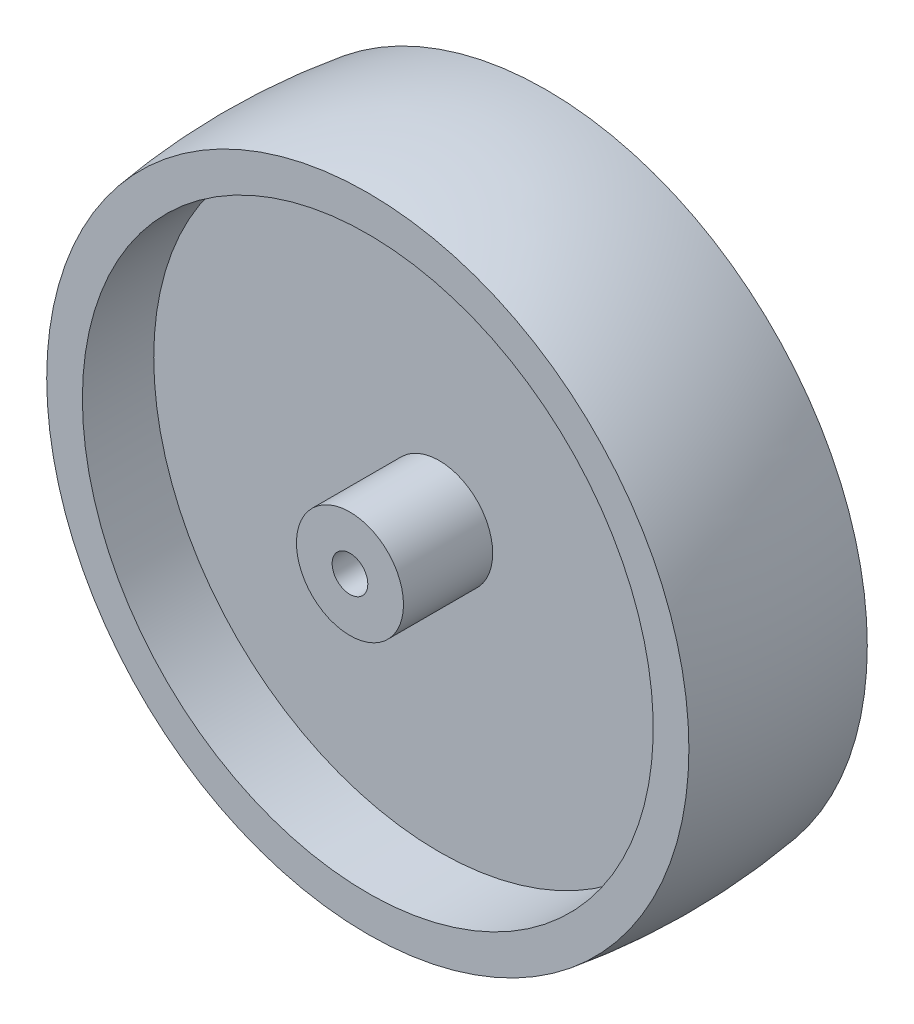
SolidWorks part; units mm, degrees
ref_plane "Piano frontale" through (0, 0, 0) normal (0, 0, 1) x (1, 0, 0)
ref_plane "Piano superiore" through (0, 0, 0) normal (0, 1, 0) x (1, 0, 0)
ref_plane "Piano destro" through (0, 0, 0) normal (1, 0, 0) x (0, 0, -1)
sketch "Schizzo1" plane through (0, 0, 0) normal (0, 0, 1) x (1, 0, 0)
  circle A0 centre (0, 0) radius 15
  circle A1 centre (0, 0) radius 5
  dimension "D1" = 30
  dimension "D2" = 10
extrude "Estrusione-Estrusione1" add sketch "Schizzo1" along normal blind 60
ref_plane "Piano1" through (0, 0, 30) normal (0, 0, 1) x (1, 0, 0)
sketch "Schizzo2" plane through (0, 0, 30) normal (0, 0, 1) x (1, 0, 0)
  circle A0 centre (0, 0) radius 80
  circle A1 centre (0, 0) radius 15
  circle A2 centre (0, 0) radius 15 construction
  dimension "D1" = 160
extrude "Estrusione-Estrusione2" add sketch "Schizzo2" along normal mid plane 10
sketch "Schizzo3" plane through (0, 0, 0) normal (1, 0, 0) x (0, 0, -1)
  line L0 (-5, 80) -> (-55, 80)
  line L1 (-35, 80) -> (-35, -80) construction
  line L2 (-55, 80) -> (-55, 90)
  line L3 (-5, 80) -> (-5, 90)
  line L4 (0, 0) -> (-85.456, 0) construction
  arc A0 (-5, 90) -> (-55, 90) centre (-30, -88.2554) ccw
  dimension "D3" = 360
  dimension "D1" = 50
  dimension "D2" = 20
  dimension "D4" = 10
revolve "Rivoluzione1" add sketch "Schizzo3" angle 360 about L4
